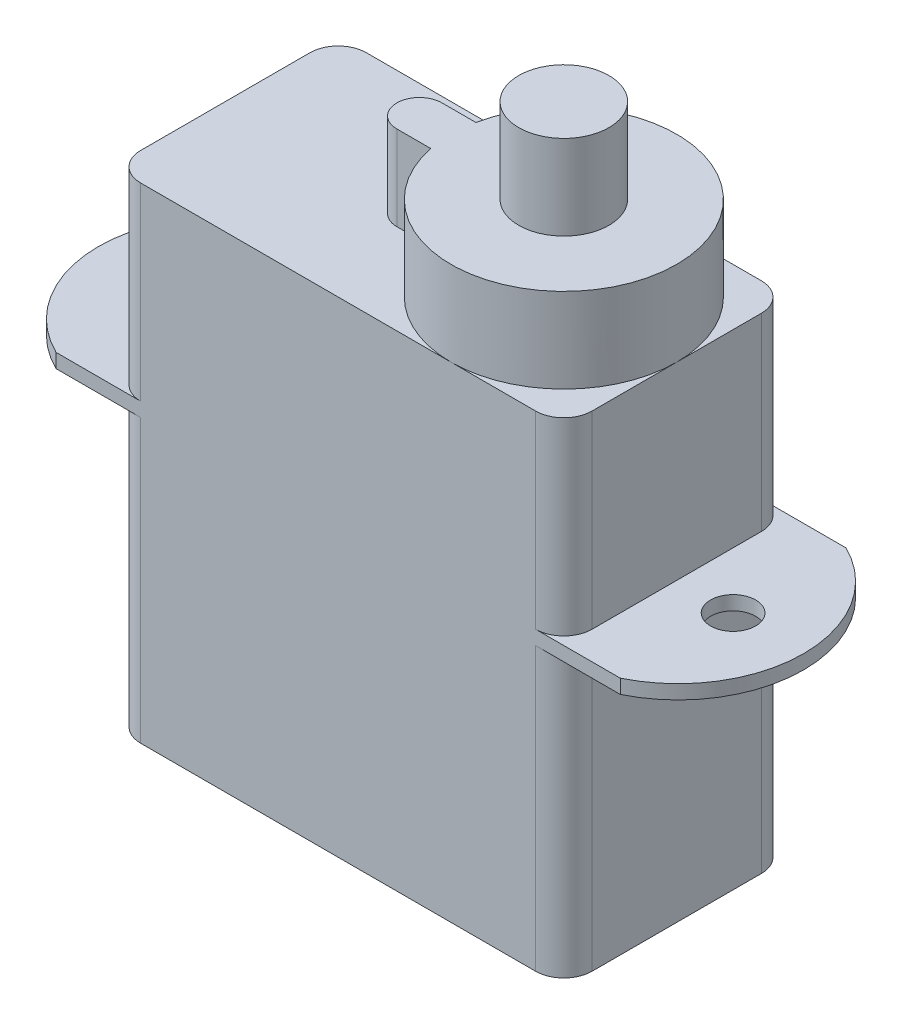
SolidWorks part; units mm, degrees
ref_plane "前视基准面" through (0, 0, 0) normal (0, 0, 1) x (1, 0, 0)
ref_plane "上视基准面" through (0, 0, 0) normal (0, 1, 0) x (1, 0, 0)
ref_plane "右视基准面" through (0, 0, 0) normal (1, 0, 0) x (0, 0, -1)
other "Configuration Table"
sketch "草图1" plane through (0, 0, 0) normal (0, 1, 0) x (1, 0, 0)
  line L1 (-7, -4) -> (7, -4)
  line L2 (-8, -3) -> (-8, 3)
  line L3 (-7, 4) -> (7, 4)
  line L4 (8, -3) -> (8, 3)
  line L5 (-8, -4) -> (8, 4) construction
  line L6 (-8, 4) -> (8, -4) construction
  arc A0 (7, -4) -> (8, -3) centre (7, -3) ccw
  arc A1 (7, 4) -> (8, 3) centre (7, 3) cw
  arc A2 (-7, -4) -> (-8, -3) centre (-7, -3) cw
  arc A3 (-8, 3) -> (-7, 4) centre (-7, 3) cw
  point P0 (0, 0)
  dimension "D3" = 1
  dimension "D1" = 8
  dimension "D2" = 16
extrude "凸台-拉伸1" add sketch "草图1" along normal blind 10
sketch "草图2" plane through (0, 10, 0) normal (0, 1, 0) x (1, 0, 0)
  line L0 (-19.5651, 0) -> (15.6225, 0) construction
  line L1 (-10, -4) -> (10, -4)
  line L3 (-10, 4) -> (10, 4)
  line L5 (-10, -4) -> (10, 4) construction
  line L6 (-10, 4) -> (10, -4) construction
  line L7 (0, -11.2951) -> (0, 14.7272) construction
  arc A0 (-10, 4) -> (-10, -4) centre (-8.05, 0) ccw
  arc A1 (10, 4) -> (10, -4) centre (8.05, 0) cw
  circle A4 centre (-10, 0) radius 0.8
  circle A5 centre (10, 0) radius 0.8
  point P0 (0, 0)
  point P14 (-12.5, 0)
  dimension "D2" = 12.5
  dimension "D3" = 1.6
  dimension "D4" = 10
  dimension "D1" = 20
  dimension "D5" = 8
extrude "凸台-拉伸2" add sketch "草图2" along normal blind 0.5
sketch "草图3" plane through (0, 10.5, 0) normal (0, 1, 0) x (1, 0, 0)
  line L4 (7, 4) -> (-7, 4)
  line L5 (8, -3) -> (8, 3)
  line L6 (-7, -4) -> (7, -4)
  line L7 (-8, 3) -> (-8, -3)
  line L8 (7, 4) -> (-7, 4)
  line L9 (8, -3) -> (8, 3)
  line L10 (-7, -4) -> (7, -4)
  line L11 (-8, 3) -> (-8, -3)
  arc A4 (8, 3) -> (7, 4) centre (7, 3) ccw
  arc A5 (7, -4) -> (8, -3) centre (7, -3) ccw
  arc A6 (-8, -3) -> (-7, -4) centre (-7, -3) ccw
  arc A7 (-7, 4) -> (-8, 3) centre (-7, 3) ccw
  arc A8 (8, 3) -> (7, 4) centre (7, 3) ccw
  arc A9 (7, -4) -> (8, -3) centre (7, -3) ccw
  arc A10 (-8, -3) -> (-7, -4) centre (-7, -3) ccw
  arc A11 (-7, 4) -> (-8, 3) centre (-7, 3) ccw
  dimension "D1" = 0
extrude "凸台-拉伸3" add sketch "草图3" along normal blind 6.7
sketch "草图4" plane through (0, 17.2, 0) normal (0, 1, 0) x (1, 0, 0)
  line L0 (12.6092, 0) -> (-12.7443, 0) construction
  line L1 (8, -3) -> (8, 3) construction
  line L2 (7, 4) -> (-7, 4) construction
  line L3 (-1.1192, 0.8) -> (0.0808, 0.8)
  line L4 (-1.1192, -0.8) -> (0.0808, -0.8)
  arc A0 (0.0808, -0.8) -> (0.0808, 0.8) centre (4, 0) ccw
  arc A1 (-1.1192, 0.8) -> (-1.1192, -0.8) centre (-1.1192, 0) ccw
  dimension "D1" = 1.6
  dimension "D2" = 1.2
extrude "凸台-拉伸4" add sketch "草图4" along normal blind 3
sketch "草图5" plane through (0, 20.2, 0) normal (0, 1, 0) x (1, 0, 0)
  circle A0 centre (4, 0) radius 1.6
  dimension "D1" = 3.2
extrude "凸台-拉伸5" add sketch "草图5" along normal blind 3
